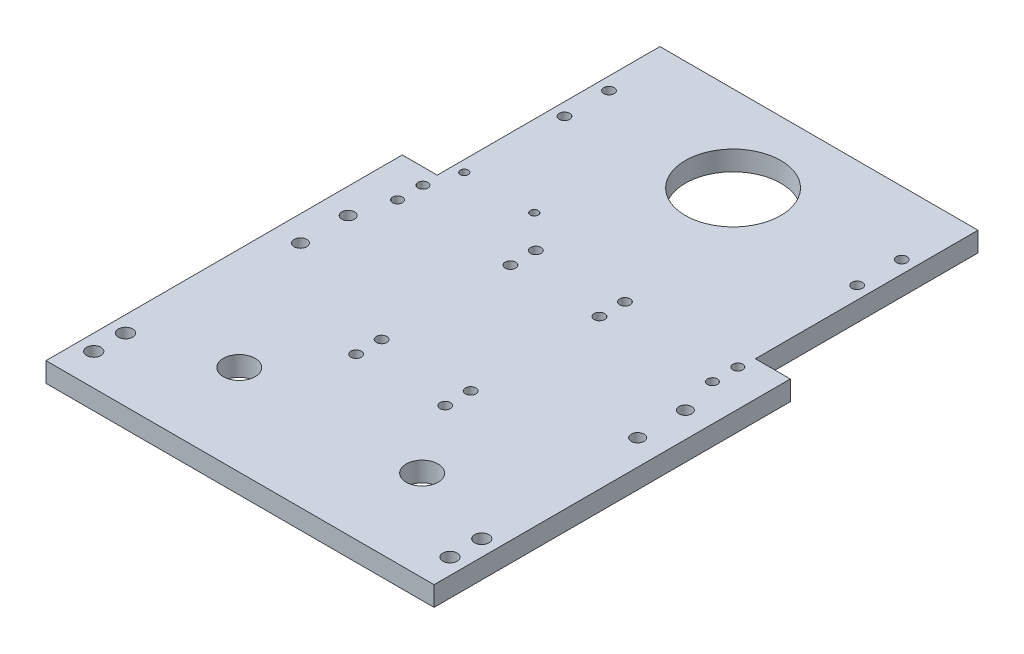
SolidWorks part; units mm, degrees
ref_plane "Front Plane" through (0, 0, 0) normal (0, 0, 1) x (1, 0, 0)
ref_plane "Top Plane" through (0, 0, 0) normal (0, 1, 0) x (1, 0, 0)
ref_plane "Right Plane" through (0, 0, 0) normal (1, 0, 0) x (0, 0, -1)
sketch "Sketch1" plane through (0, 0, 0) normal (0, 1, 0) x (1, 0, 0)
  line L1 (-61, 56) -> (61, 56)
  line L2 (-61, 56) -> (-61, -56)
  line L3 (-61, -56) -> (61, -56)
  line L4 (61, 56) -> (61, -56)
  line L5 (-61, 56) -> (61, -56) construction
  line L6 (-61, -56) -> (61, 56) construction
  point P0 (0, 0)
  dimension "D1" = 122
  dimension "D2" = 112
extrude "Boss-Extrude1" add sketch "Sketch1" along normal blind 6.2
sketch "Sketch2" plane through (0, 0, 0) normal (0, 1, 0) x (1, 0, 0)
  line L0 (61, 56) -> (-61, 56) construction
  line L1 (-50, 56) -> (50, 56)
  line L2 (-50, 56) -> (-50, 126)
  line L3 (-50, 126) -> (50, 126)
  line L4 (50, 56) -> (50, 126)
  line L5 (0, -3.41) -> (0, 3.41) construction
  dimension "D1" = 100
  dimension "D2" = 50
  dimension "D3" = 70
extrude "Boss-Extrude2" add sketch "Sketch2" along normal blind 6.2
sketch "Sketch3" plane through (0, 6.2, 0) normal (0, 1, 0) x (1, 0, 0)
  line L0 (-50, 56) -> (50, 56) construction
  line L1 (-50, 126) -> (-50, 56) construction
  line L3 (0, -3.41) -> (0, 3.41) construction
  line L4 (0, 126) -> (0, 56) construction
  line L5 (50, 126) -> (-50, 126) construction
  line L6 (0, 99) -> (50, 99) construction
  line L7 (50, 56) -> (50, 126) construction
  circle A0 centre (-46.5, 61) radius 1.25
  circle A1 centre (-24.5, 61) radius 1.25
  circle A3 centre (-46.013, 106) radius 1.65
  circle A6 centre (0, 99) radius 15
  circle A7 centre (-46.013, 92) radius 1.65
  circle A8 centre (46.013, 92) radius 1.65
  circle A9 centre (46.013, 106) radius 1.65
  dimension "D1" = 2.5
  dimension "D2" = 2.5
  dimension "D16" = 3.3
  dimension "D17" = 30
  dimension "D3" = 5
  dimension "D4" = 5
  dimension "D5" = 22
  dimension "D6" = 3.5
  dimension "D18" = 43
  dimension "D7" = 46.013
  dimension "D8" = 7
extrude "Cut-Extrude1" cut sketch "Sketch3" against normal through all
sketch "Sketch4" plane through (0, 6.2, 0) normal (0, 1, 0) x (1, 0, 0)
  line L0 (-46.5, 61) -> (-24.5, 61) construction
  line L1 (-35.5, 61) -> (-35.5, 13.896) construction
  line L2 (-50, 56) -> (-61, 56) construction
  line L3 (61, 56) -> (50, 56) construction
  line L4 (0, -3.41) -> (0, 3.41) construction
  line L5 (-15.5456, 22.75) -> (18.1861, 22.75) construction
  line L6 (0, 0) -> (0, 106.2525) construction
  circle A0 centre (-49.5, 51) radius 1.55
  circle A1 centre (-21.5, 51) radius 1.55 construction
  circle A2 centre (-21.5, 43) radius 1.55 construction
  circle A3 centre (-49.5, 43) radius 1.55
  circle A4 centre (-14, 2.5) radius 1.65
  circle A5 centre (14, 2.5) radius 1.65
  circle A6 centre (14, -5.5) radius 1.65
  circle A7 centre (-14, -5.5) radius 1.65
  circle A8 centre (-14, 51) radius 1.65
  circle A9 centre (14, 51) radius 1.65
  circle A10 centre (14, 43) radius 1.65
  circle A11 centre (-14, 43) radius 1.65
  circle A12 centre (49.5, 43) radius 1.55
  circle A13 centre (49.5, 51) radius 1.55
  dimension "D1" = 3.1
  dimension "D8" = 3.3
  dimension "D9" = 14
  dimension "D2" = 5
  dimension "D5" = 53.5
  dimension "D10" = 14
  dimension "D11" = 20.25
  dimension "D3" = 2
  dimension "D4" = 2
  dimension "D6" = 2
  dimension "D7" = 2
extrude "Cut-Extrude2" cut sketch "Sketch4" against normal through all
sketch "Sketch5" plane through (0, 6.2, 0) normal (0, 1, 0) x (1, 0, 0)
  line L0 (-61, 56) -> (-61, -56) construction
  line L1 (-50, 56) -> (-61, 56) construction
  line L2 (0, -3.41) -> (0, 3.41) construction
  circle A0 centre (-53, 31) radius 2
  circle A1 centre (-53, 16) radius 2
  circle A2 centre (53, 16) radius 2
  circle A3 centre (53, 31) radius 2
  dimension "D3" = 4
  dimension "D4" = 4
  dimension "D1" = 8
  dimension "D2" = 8
  dimension "D5" = 15
  dimension "D6" = 25
extrude "Cut-Extrude3" cut sketch "Sketch5" against normal blind 10
sketch "Sketch6" plane through (0, 6.2, 0) normal (0, 1, 0) x (1, 0, 0)
  line L0 (0, 55.945) -> (0, -50.7895) construction
  line L1 (0, -3.41) -> (0, 3.41) construction
  line L2 (-28.75, -27.5) -> (28.75, -27.5) construction
  line L3 (61, 56) -> (50, 56) construction
  circle A0 centre (-28.75, -27.5) radius 5
  circle A1 centre (28.75, -27.5) radius 5
  dimension "D4" = 10
  dimension "D5" = 10
  dimension "D1" = 83.5
  dimension "D2" = 28.75
  dimension "D3" = 28.75
extrude "Cut-Extrude4" cut sketch "Sketch6" against normal blind 10
sketch "Sketch7" plane through (0, 6.2, 0) normal (0, 1, 0) x (1, 0, 0)
  line L0 (-61, 56) -> (-61, -56) construction
  line L1 (-61, -56) -> (61, -56) construction
  line L2 (0, -3.41) -> (0, 3.41) construction
  circle A0 centre (-56, -36) radius 2.25
  circle A1 centre (-56, -46) radius 2.25
  circle A2 centre (56, -46) radius 2.25
  circle A3 centre (56, -36) radius 2.25
  dimension "D5" = 4.5
  dimension "D6" = 4.5
  dimension "D1" = 5
  dimension "D3" = 10
  dimension "D4" = 10
extrude "Cut-Extrude5" cut sketch "Sketch7" against normal through all
equation "\"D2@Sketch2\"=\"D1@Sketch2\"/2"
equation "\"D2@Sketch3\"=\"D1@Sketch3\""
equation "\"D4@Sketch3\"=\"D3@Sketch3\""
equation "\"D6@Sketch7\"=\"D5@Sketch7\""
